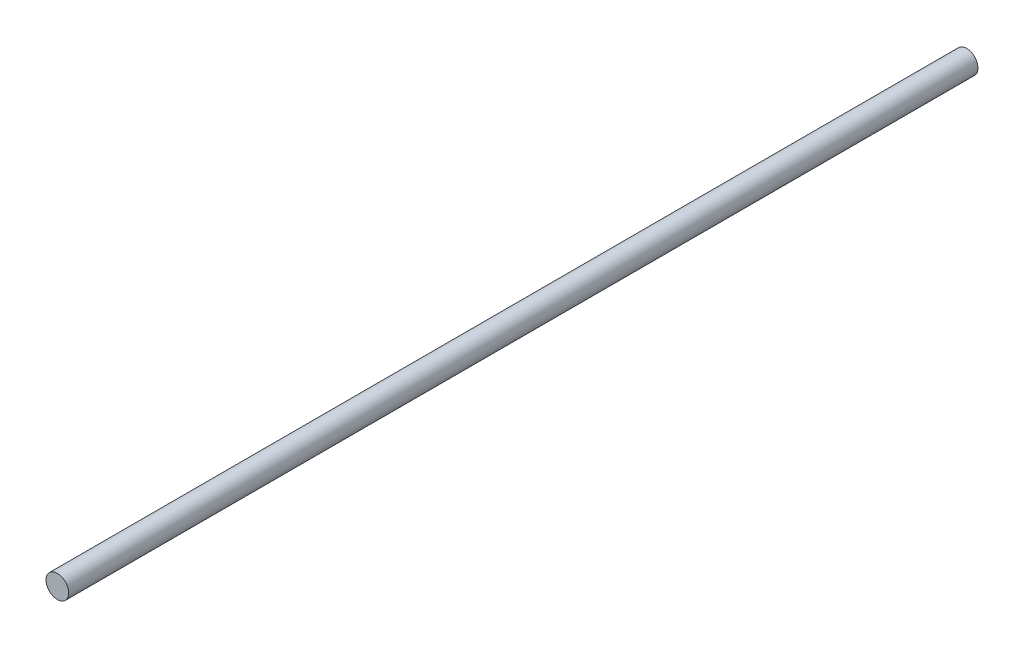
SolidWorks part; units mm, degrees
ref_plane "정면" through (0, 0, 0) normal (0, 0, 1) x (1, 0, 0)
ref_plane "윗면" through (0, 0, 0) normal (0, 1, 0) x (1, 0, 0)
ref_plane "우측면" through (0, 0, 0) normal (1, 0, 0) x (0, 0, -1)
sketch "스케치1" plane through (0, 0, 0) normal (0, 0, 1) x (1, 0, 0)
  circle A0 centre (0, 0) radius 2.5
  dimension "D1" = 5
extrude "보스-돌출1" add sketch "스케치1" along normal blind 200
